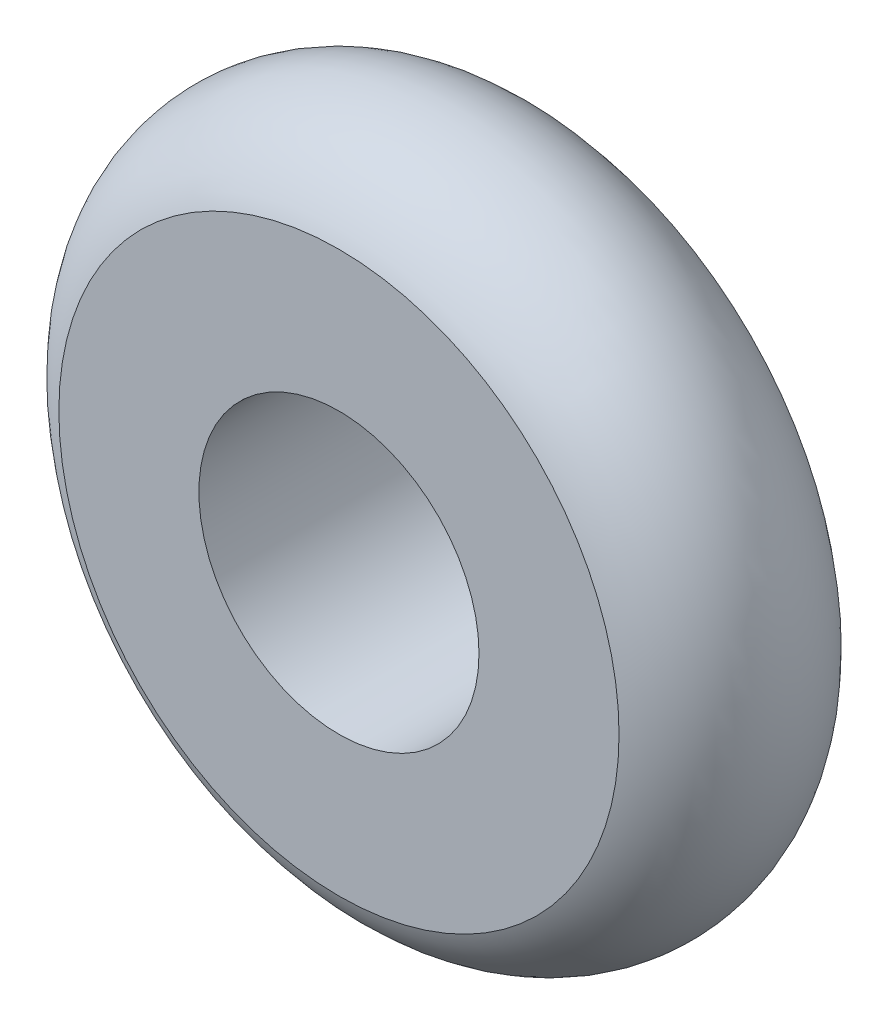
SolidWorks part; units mm, degrees
ref_plane "前视基准面" through (0, 0, 0) normal (0, 0, 1) x (1, 0, 0)
ref_plane "上视基准面" through (0, 0, 0) normal (0, 1, 0) x (1, 0, 0)
ref_plane "右视基准面" through (0, 0, 0) normal (1, 0, 0) x (0, 0, -1)
sketch "草图1" plane through (0, 0, 0) normal (0, 1, 0) x (1, 0, 0)
  line L0 (0, 0) -> (0, 88.5202) construction
  line L1 (0, 0) -> (130.9696, 0) construction
  line L2 (8, 3) -> (8, 2.5) construction
  line L3 (4, 3) -> (8, 3)
  line L4 (4, 3) -> (4, -3)
  line L5 (4, -3) -> (8, -3)
  line L6 (10, 2.5) -> (10, -2.5) construction
  line L7 (8, 2.5) -> (10, 2.5) construction
  line L8 (8, -2.5) -> (10, -2.5) construction
  line L9 (8, -3) -> (8, -2.5) construction
  arc A0 (8, -3) -> (8, 3) centre (6.75, 0) ccw
  dimension "D1" = 4
  dimension "D2" = 6
  dimension "D3" = 10
  dimension "D4" = 4
  dimension "D5" = 5
revolve "旋转1" add sketch "草图1" angle 360 about L0
